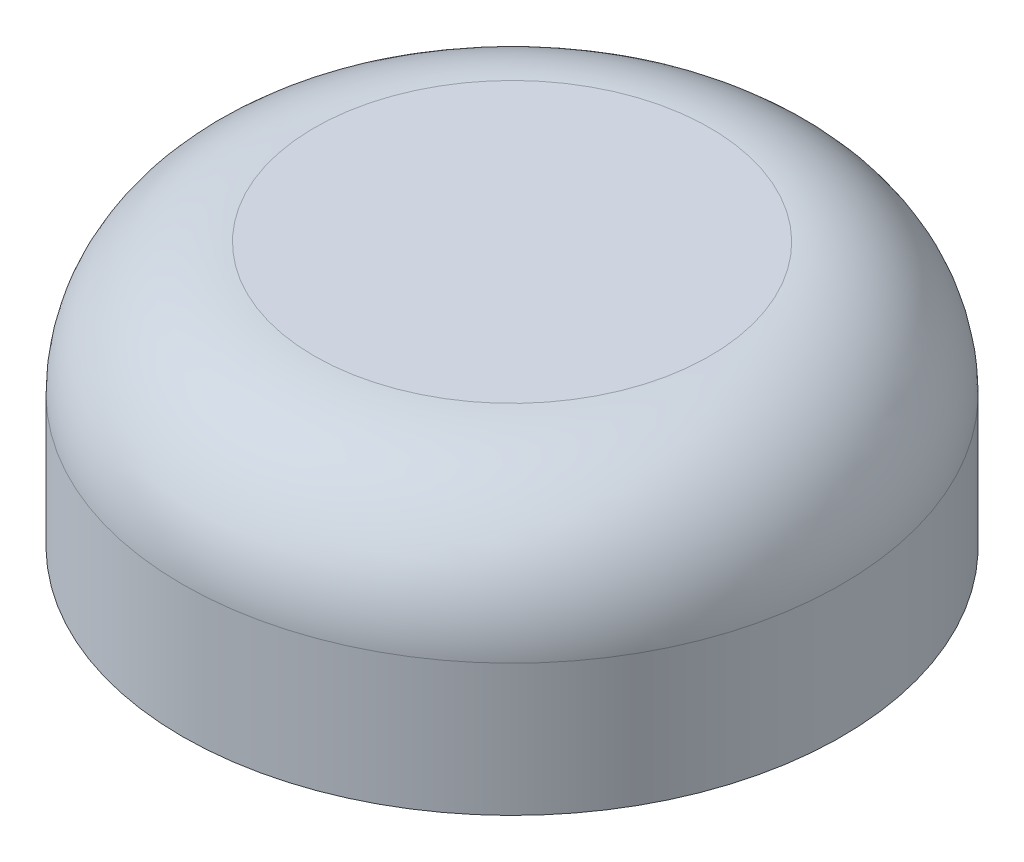
SolidWorks part; units mm, degrees
ref_plane "Alzado" through (0, 0, 0) normal (0, 0, 1) x (1, 0, 0)
ref_plane "Planta" through (0, 0, 0) normal (0, 1, 0) x (1, 0, 0)
ref_plane "Vista lateral" through (0, 0, 0) normal (1, 0, 0) x (0, 0, -1)
sketch "Croquis1" plane through (0, 0, 0) normal (0, 1, 0) x (1, 0, 0)
  circle A0 centre (0, 0) radius 2.5
extrude "Saliente-Extruir1" add sketch "Croquis1" along normal blind 2
fillet "Redondeo1" radius 1 1 edges at (0, 2, 2.5)
sketch "Croquis2" plane through (0, 0, 0) normal (0, -1, 0) x (1, 0, 0)
  circle A0 centre (0, 0) radius 1.5
extrude "Cortar-Extruir1" cut sketch "Croquis2" against normal blind 1
